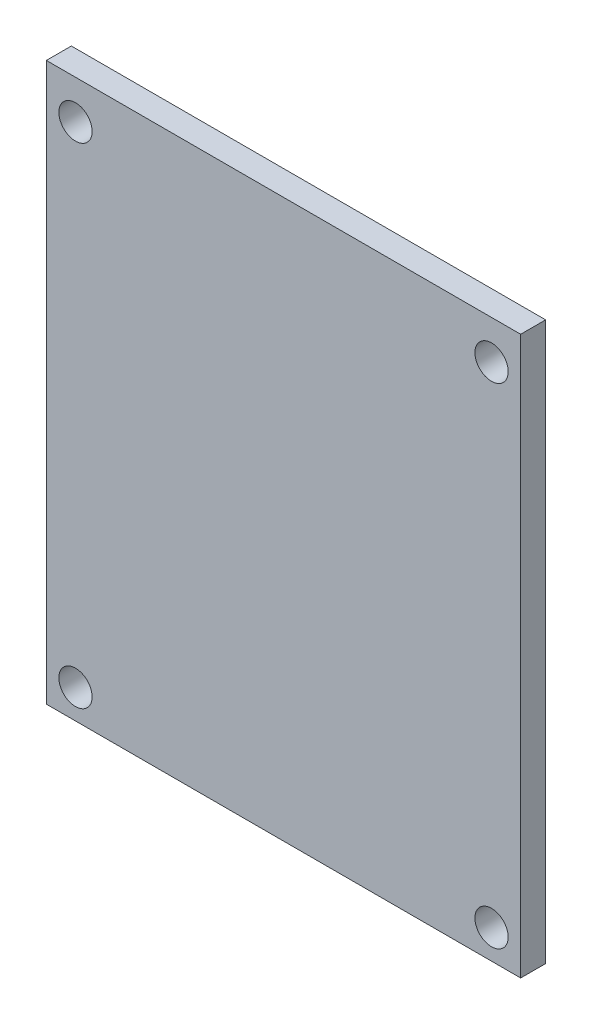
SolidWorks part; units mm, degrees
ref_plane "Přední rovina" through (0, 0, 0) normal (0, 0, 1) x (1, 0, 0)
ref_plane "Horní rovina" through (0, 0, 0) normal (0, 1, 0) x (1, 0, 0)
ref_plane "Pravá rovina" through (0, 0, 0) normal (1, 0, 0) x (0, 0, -1)
sketch "Skica1" plane through (0, 0, 0) normal (0, 0, 1) x (1, 0, 0)
  line L1 (0, 0) -> (57, 0)
  line L2 (0, 0) -> (0, 67)
  line L3 (0, 67) -> (57, 67)
  line L4 (57, 0) -> (57, 67)
  circle A0 centre (3.5, 62.3502) radius 2
  circle A1 centre (53.5, 62.3502) radius 2
  circle A2 centre (53.5, 3.5) radius 2
  circle A3 centre (3.5, 3.5) radius 2
  point P13 (0, 0)
  point P14 (0, 0)
  point P15 (0, 0)
  point P16 (0, 0)
  dimension "D5" = 4
  dimension "D1" = 67
  dimension "D2" = 57
  dimension "D3" = 3.5
  dimension "D4" = 3.5
  dimension "D6" = 50
  dimension "D7" = 58.8502
  dimension "D8" = 3.5
  dimension "D9" = 3.5
  dimension "D10" = 4.6498
extrude "Přidat vysunutím1" add sketch "Skica1" along normal blind 3
sketch "Skica2" plane through (0, 0, 0) normal (0, 0, -1) x (-1, 0, 0)
  text T0 "<r90>L</r>" font "Century Gothic" height 20
  point P1 (-21.641, 28.7979)
  point P2 (0, 0)
  point P3 (0, 0)
extrude "Přidat vysunutím2" add sketch "Skica2" along normal blind 1
